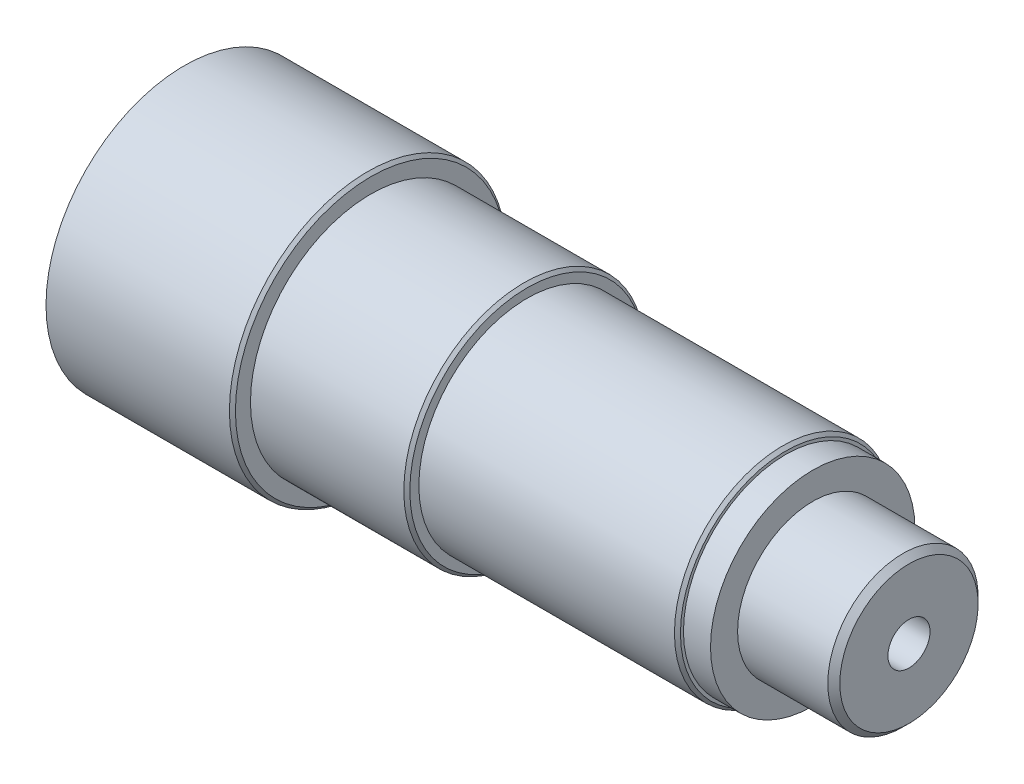
SolidWorks part; units mm, degrees
ref_plane "Plan de face" through (0, 0, 0) normal (0, 0, 1) x (1, 0, 0)
ref_plane "Plan de dessus" through (0, 0, 0) normal (0, 1, 0) x (1, 0, 0)
ref_plane "Plan de droite" through (0, 0, 0) normal (1, 0, 0) x (0, 0, -1)
sketch "Esquisse1" plane through (0, 0, 0) normal (0, 0, 1) x (1, 0, 0)
  line L0 (-47.211, 0) -> (113.2126, 0) construction
  line L1 (-44, 23) -> (-13, 23)
  line L2 (-13, 23) -> (-13, 20)
  line L3 (-13, 20) -> (13, 20)
  line L4 (13, 20) -> (13, 18)
  line L5 (13, 18) -> (56, 18)
  line L6 (56, 18) -> (56, 17)
  line L7 (56, 17) -> (60.5, 17)
  line L8 (60.5, 17) -> (60.5, 12.5)
  line L9 (60.5, 12.5) -> (76.5, 12.5)
  line L10 (76.5, 12.5) -> (76.5, 0)
  line L11 (76.5, 0) -> (-44, 0)
  line L12 (-44, 23) -> (-44, 0)
  line L13 (-13, 20) -> (0, 0) construction
  line L14 (0, 0) -> (0, 20) construction
  dimension "D1" = 46
  dimension "D2" = 40
  dimension "D3" = 31
  dimension "D4" = 26
  dimension "D5" = 36
  dimension "D6" = 43
  dimension "D7" = 34
  dimension "D8" = 4.5
  dimension "D9" = 16
  dimension "D10" = 25
revolve "Révolution1" add sketch "Esquisse1" angle 360 about L0
chamfer "Chanfrein1" distance 0.5 angle 45 3 edges at (13, 0, 20) (-13, 0, 23) (56, 0, 18)
chamfer "Chanfrein2" distance 1 angle 45 1 edges at (76.5, 0, 12.5)
hole_wizard "Trou taraudé M8x1.01" positions "Esquisse3" profile "Esquisse2" tap size "M8x1.0" standard "ISO"
sketch "Esquisse3" plane through (76.5, 0, 0) normal (1, 0, 0) x (0, 0, -1)
  point P0 (0, 0)
cosmetic thread "Filetage de perçage1" parameters "D1"=18, "D2"=8
sketch "Esquisse2" plane through (76.5, 0, 0) normal (0, 1, 0) x (0, 0, -1)
  line L0 (0, 0) -> (0, 25.103)
  line L1 (0, 25.103) -> (3.5, 23)
  line L2 (3.5, 23) -> (3.5, 0)
  line L5 (3.5, 0) -> (0, 0)
  line L10 (0, 25.103) -> (-3.5, 23) construction
  line L11 (0, -6.35) -> (0, 107.95) construction
  dimension "Diamètre du trou pour taraudage" = 7
  dimension "Profondeur du trou pour taraudage" = 23
  dimension "Angle de pointe" = 118
